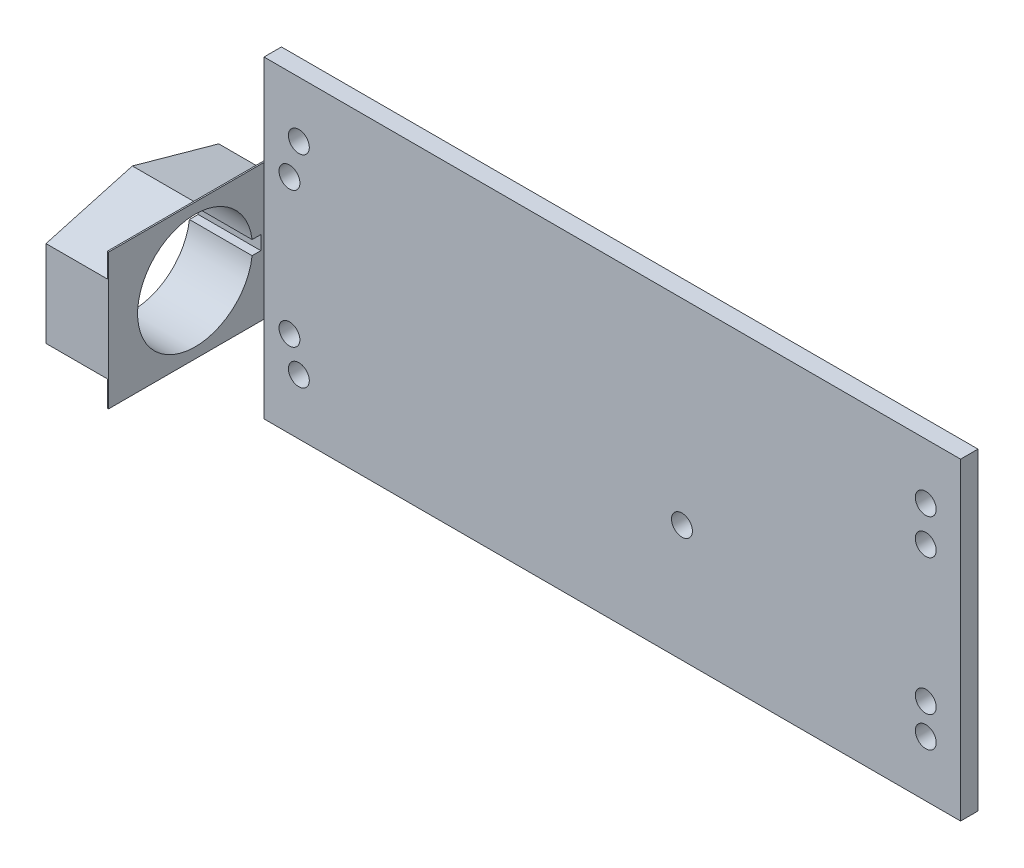
SolidWorks part; units mm, degrees
ref_plane "Front Plane" through (0, 0, 0) normal (0, 0, 1) x (1, 0, 0)
ref_plane "Top Plane" through (0, 0, 0) normal (0, 1, 0) x (1, 0, 0)
ref_plane "Right Plane" through (0, 0, 0) normal (1, 0, 0) x (0, 0, -1)
sketch "Sketch1" plane through (0, 0, 0) normal (0, 0, 1) x (1, 0, 0)
  line L0 (-446.0594, 240.1188) -> (-446.0594, 195.1188) construction
  line L1 (-496.0594, 240.1188) -> (-396.0594, 240.1188)
  line L2 (-496.0594, 240.1188) -> (-496.0594, 195.1188)
  line L3 (-496.0594, 195.1188) -> (-396.0594, 195.1188)
  line L4 (-396.0594, 240.1188) -> (-396.0594, 195.1188)
  circle A0 centre (-491.0594, 232.1188) radius 1.5
  circle A1 centre (-491.0594, 203.1188) radius 1.5
  circle A2 centre (-401.0594, 203.1188) radius 1.5
  circle A3 centre (-401.0594, 232.1188) radius 1.5
  dimension "D6" = 3
  dimension "D7" = 3
  dimension "D8" = 8
  dimension "D1" = 100
  dimension "D2" = 0
  dimension "D3" = 5
  dimension "D4" = 8
  dimension "D5" = 45
extrude "Boss-Extrude2" add sketch "Sketch1" along normal blind 2.5
sketch "Sketch2" plane through (0, 0, 2.5) normal (0, 0, 1) x (1, 0, 0)
  line L0 (-496.0594, 240.1188) -> (-496.0594, 195.1188) construction
  line L1 (-396.0594, 240.1188) -> (-396.0594, 195.1188) construction
  line L2 (-496.0594, 195.1188) -> (-396.0594, 195.1188) construction
  line L3 (-396.0594, 240.1188) -> (-396.0594, 195.1188) construction
  line L4 (-396.0594, 195.1188) -> (-496.0594, 195.1188) construction
  line L5 (-496.0594, 195.1188) -> (-496.0594, 240.1188) construction
  line L6 (-496.0594, 240.1188) -> (-396.0594, 195.1188) construction
  line L7 (-396.0594, 195.1188) -> (-396.0594, 240.1188) construction
  line L8 (-396.0594, 240.1188) -> (-496.0594, 195.1188) construction
  line L9 (-396.0594, 217.6188) -> (-496.0594, 217.6188) construction
  line L10 (-400.9094, 240.1188) -> (-400.9094, 195.1188) construction
  line L11 (-396.0594, 240.1188) -> (-496.0594, 240.1188) construction
  line L12 (-492.4094, 195.1188) -> (-492.4094, 227.0188) construction
  line L13 (-401.0594, 227.0188) -> (-401.0594, 207.5188) construction
  line L14 (-401.0594, 227.0188) -> (-496.0594, 227.0188) construction
  line L15 (-401.0594, 207.5188) -> (-496.0594, 207.5188) construction
  line L16 (-492.4094, 238.4763) -> (-492.4094, 240.1188) construction
  circle A0 centre (-436.0594, 211.9188) radius 1.5
  circle A6 centre (-401.0594, 227.0188) radius 1.5
  circle A7 centre (-401.0594, 207.5188) radius 1.5
  circle A8 centre (-492.4094, 207.5188) radius 1.5
  circle A9 centre (-492.4094, 227.0188) radius 1.5
  dimension "D1" = 91.5
  dimension "D4" = 4.85
  dimension "D5" = 19.5
  dimension "D6" = 12.4
  dimension "D7" = 3
  dimension "D8" = 3
  dimension "D9" = 3
  dimension "D10" = 3
  dimension "D2" = 60
  dimension "D3" = 16.8
extrude "Cut-Extrude2" cut sketch "Sketch2" along normal blind 13 and the other way blind 17
sketch "Sketch3" plane through (0, 0, 0) normal (0, 0, 1) x (1, 0, 0)
  line L0 (-496.0594, 240.1188) -> (-496.0594, 195.1188) construction
  line L1 (-496.0594, 207.5188) -> (-505.0594, 207.5188)
  line L2 (-496.0594, 207.5188) -> (-496.0594, 227.0188)
  line L3 (-496.0594, 227.0188) -> (-505.0594, 227.0188)
  line L4 (-505.0594, 207.5188) -> (-505.0594, 227.0188)
  circle A0 centre (-492.4094, 207.5188) radius 1.5 construction
  circle A1 centre (-492.4094, 227.0188) radius 1.5 construction
  circle A3 centre (-492.4094, 227.0188) radius 1.5 construction
  dimension "D1" = 9
  dimension "D2" = 0
  dimension "D3" = 0
extrude "Boss-Extrude3" add sketch "Sketch3" along normal blind 24.8
sketch "Sketch4" plane through (-505.0594, 0, 0) normal (-1, 0, 0) x (0, 0, 1)
  line L0 (0, 227.0188) -> (0, 207.5188) construction
  line L1 (0, 207.5188) -> (24.8, 207.5188) construction
  line L2 (24.8, 207.5188) -> (24.8, 227.0188) construction
  line L3 (24.8, 227.0188) -> (0, 207.5188) construction
  line L4 (0, 207.5188) -> (0, 227.0188) construction
  line L5 (0, 227.0188) -> (24.8, 207.5188) construction
  line L6 (24.8, 207.5188) -> (12.4, 217.2688) construction
  line L7 (12.4, 217.2688) -> (24.8, 217.2688) construction
  line L8 (24.8, 217.2688) -> (0, 217.2688) construction
  line L9 (0, 217.2688) -> (0, 225.2688)
  line L10 (0, 217.2688) -> (0, 209.2688)
  line L11 (0, 225.2688) -> (24.8, 225.2688) construction
  line L12 (24.8, 225.2688) -> (0, 209.2688) construction
  line L13 (0, 209.2688) -> (24.8, 209.2688) construction
  line L14 (12.4, 207.5188) -> (12.4, 227.0188) construction
  line L15 (24.8, 227.0188) -> (0, 227.0188) construction
  line L16 (12.4, 227.0188) -> (0, 223.5695)
  line L17 (0, 223.5695) -> (0, 211.1506)
  line L18 (0, 211.1506) -> (12.4, 207.5188)
  line L19 (12.4, 207.5188) -> (24.8, 211.1506)
  line L20 (24.8, 211.1506) -> (24.8, 223.5695)
  line L21 (24.8, 223.5695) -> (12.4, 227.0188)
  line M1 (0, 227.0188) -> (0, 207.5188)
  line M2 (0, 207.5188) -> (24.8, 207.5188)
  line M3 (24.8, 207.5188) -> (24.8, 227.0188)
  line M4 (24.8, 227.0188) -> (0, 227.0188)
  dimension "D1" = 8
  dimension "D2" = 8
extrude "Cut-Extrude3" cut sketch "Sketch4" against normal blind 8.8 contours L16 M4 M1 | L21 M3 M4 | L19 M2 M3 | L18 L10 M1 M2
sketch "Sketch7" plane through (0, 0, 0) normal (1, 0, 0) x (0, 0, -1)
  line L0 (-12.4, 227.0188) -> (-12.4, 207.5188) construction
  line L1 (-12.4, 207.5188) -> (-24.8, 207.5188) construction
  line L2 (-24.8, 207.5188) -> (0, 227.0188) construction
  circle A0 centre (-12.4, 217.2688) radius 8.25
  dimension "D1" = 16.5
extrude "Cut-Extrude4" cut sketch "Sketch7" against normal blind 714.8
sketch "Sketch8" plane through (0, 0, 0) normal (1, 0, 0) x (0, 0, -1)
  line L0 (-12.4, 217.2688) -> (0, 217.3601) construction
  line L1 (0, 223.5695) -> (0, 211.1506) construction
  line L3 (-4.2108, 218.2688) -> (-2.9585, 218.2688)
  line L4 (-4.2108, 218.2688) -> (-4.2108, 216.2688)
  line L5 (-4.2108, 216.2688) -> (-2.9585, 216.2688)
  line L6 (-2.9585, 218.2688) -> (-2.9585, 216.2688)
  circle A0 centre (-12.4, 217.2688) radius 8.25 construction
  dimension "D1" = 1
  dimension "D2" = 2
extrude "Cut-Extrude5" cut sketch "Sketch8" against normal blind 714.8
